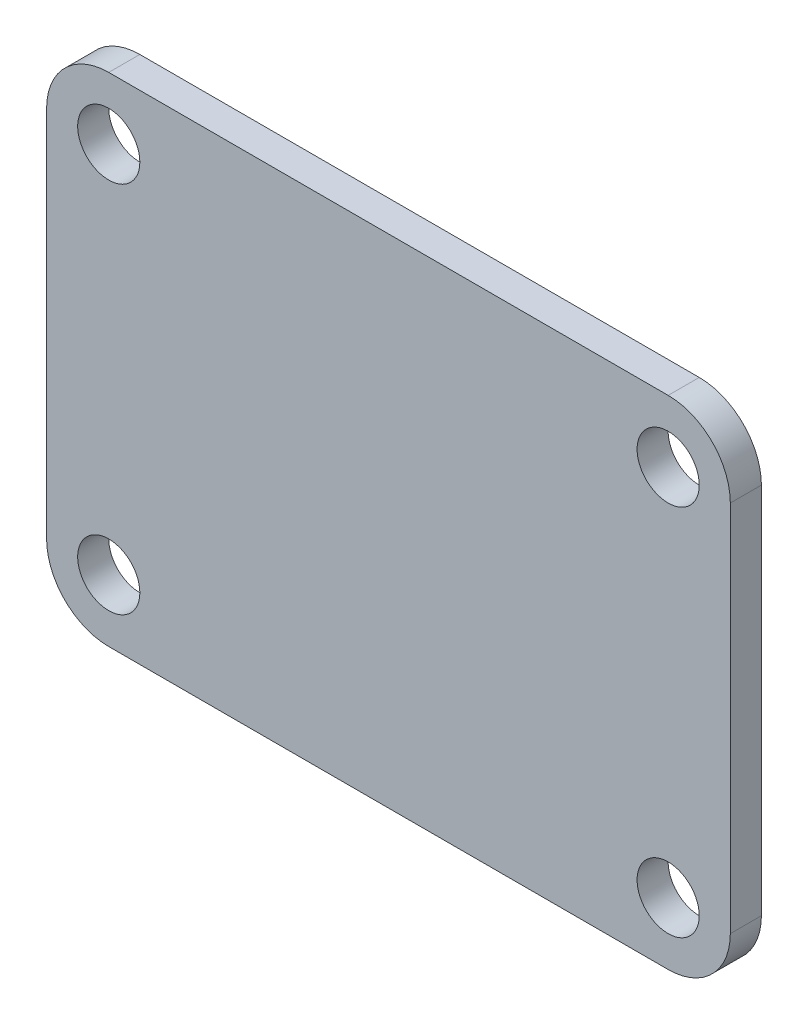
SolidWorks part; units mm, degrees
ref_plane "Front Plane" through (0, 0, 0) normal (0, 0, 1) x (1, 0, 0)
ref_plane "Top Plane" through (0, 0, 0) normal (0, 1, 0) x (1, 0, 0)
ref_plane "Right Plane" through (0, 0, 0) normal (1, 0, 0) x (0, 0, -1)
sketch "Sketch1" plane through (0, 0, 0) normal (0, 0, 1) x (1, 0, 0)
  line L0 (0, 15.24) -> (0, 0) construction
  line L1 (0, 0) -> (22.86, 0) construction
  line L2 (22.86, 0) -> (22.86, 15.24) construction
  line L3 (22.86, 15.24) -> (0, 15.24) construction
  line L4 (-2.54, 17.78) -> (-2.54, -2.54)
  line L5 (-2.54, -2.54) -> (25.4, -2.54)
  line L6 (25.4, -2.54) -> (25.4, 17.78)
  line L7 (25.4, 17.78) -> (-2.54, 17.78)
  circle A0 centre (0, 15.24) radius 1.27
  circle A1 centre (0, 0) radius 1.27
  circle A2 centre (22.86, 15.24) radius 1.27
  circle A3 centre (22.86, 0) radius 1.27
  point P0 (0, 0)
  point P1 (0, 15.24)
  point P3 (22.86, 15.24)
  point P4 (22.86, 0)
  dimension "D3" = 2.54
  dimension "D1" = 22.86
  dimension "D2" = 15.24
  dimension "D4" = 2.54
extrude "Boss-Extrude1" add sketch "Sketch1" along normal blind 1.27
fillet "Fillet1" radius 2.54 4 edges at (-2.54, -2.54, 0.635) (25.4, -2.54, 0.635) (25.4, 17.78, 0.635) (-2.54, 17.78, 0.635)
